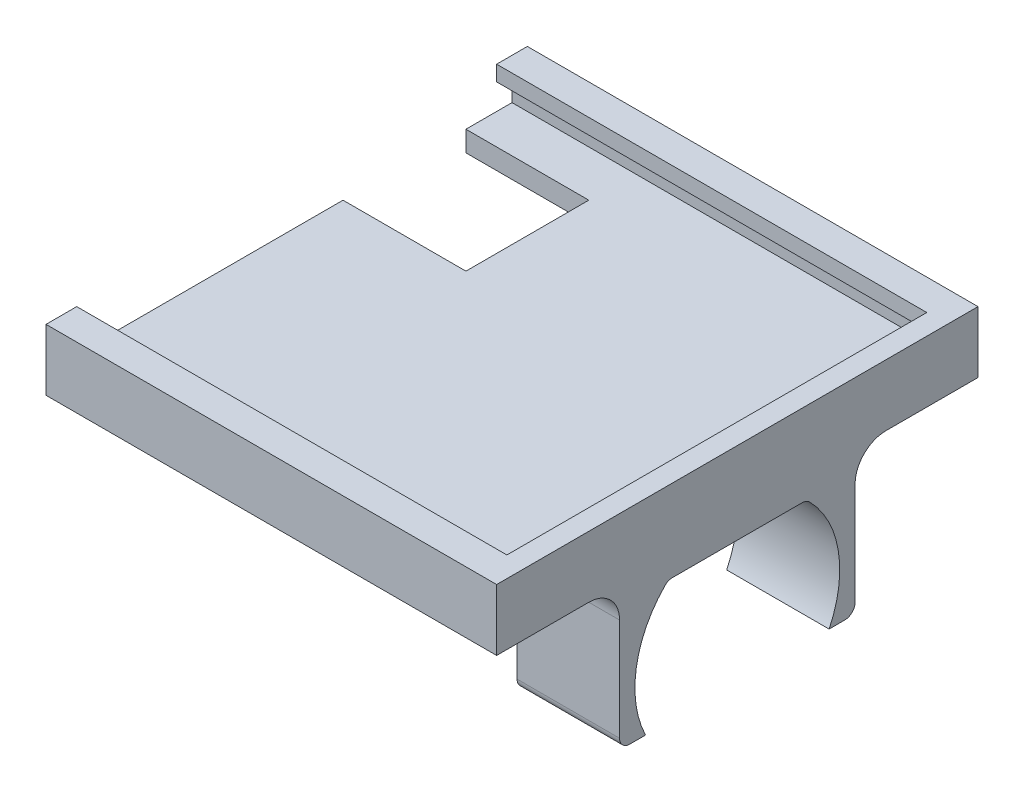
SolidWorks part; units mm, degrees
ref_plane "Front Plane" through (0, 0, 0) normal (0, 0, 1) x (1, 0, 0)
ref_plane "Top Plane" through (0, 0, 0) normal (0, 1, 0) x (1, 0, 0)
ref_plane "Right Plane" through (0, 0, 0) normal (1, 0, 0) x (0, 0, -1)
sketch "Sketch2" plane through (0, 0, 0) normal (0, 1, 0) x (1, 0, 0)
  line L1 (20, 21.5) -> (-20, 21.5)
  line L2 (20, 21.5) -> (20, -21.5)
  line L3 (20, -21.5) -> (-20, -21.5)
  line L4 (-20, 21.5) -> (-20, -21.5)
  line L5 (20, 21.5) -> (-20, -21.5) construction
  line L6 (20, -21.5) -> (-20, 21.5) construction
  point P0 (0, 0)
  dimension "D1" = 43
  dimension "D2" = 40
sketch "Sketch3" plane through (0, 0, 0) normal (0, 1, 0) x (1, 0, 0)
  line L0 (20, -21.5) -> (-20, 21.5) construction
  line L1 (-22, -23.5) -> (22, -23.5)
  line L2 (-22, -23.5) -> (-22, 23.5)
  line L3 (-22, 23.5) -> (22, 23.5)
  line L4 (22, -23.5) -> (22, 23.5)
  line L5 (-22, -23.5) -> (22, 23.5) construction
  line L6 (-22, 23.5) -> (22, -23.5) construction
  point P0 (0, 0)
  dimension "D1" = 47
  dimension "D2" = 44
extrude "Boss-Extrude1" add sketch "Sketch3" along normal blind 6
sketch "Sketch4" plane through (0, 6, 0) normal (0, 1, 0) x (1, 0, 0)
  line L1 (-22, -22) -> (20, -22)
  line L2 (-22, -22) -> (-22, 22)
  line L3 (-22, 22) -> (20, 22)
  line L4 (20, -22) -> (20, 22)
  line L5 (-22, 23.5) -> (-22, -23.5) construction
  line L7 (22, -23.5) -> (22, 23.5) construction
  line L8 (22, 23.5) -> (-22, 23.5) construction
  line L9 (-22, -23.5) -> (22, -23.5) construction
  dimension "D1" = 2
  dimension "D2" = 1.5
  dimension "D3" = 1.5
extrude "Cut-Extrude1" cut sketch "Sketch4" against normal blind 4 contours L3 L4 L1 L2
sketch "Sketch5" plane through (0, 6, 0) normal (0, 1, 0) x (1, 0, 0)
  line L0 (0, -3.3) -> (0, 3.3) construction
  line L1 (22, 20.5) -> (-22, 20.5)
  line L2 (22, 20.5) -> (22, 23.5)
  line L3 (22, 23.5) -> (-22, 23.5)
  line L4 (-22, 20.5) -> (-22, 23.5)
  line L5 (22, 20.5) -> (-22, 23.5) construction
  line L6 (22, 23.5) -> (-22, 20.5) construction
  line L7 (-22, 22) -> (20, 22) construction
  point P0 (0, 22)
extrude "Boss-Extrude2" add sketch "Sketch5" against normal blind 1.5
mirror "Mirror1" about plane through (0, 0, 0) normal (0, 0, 1) of "Boss-Extrude2"
sketch "Sketch6" plane through (0, 0, 0) normal (0, -1, 0) x (1, 0, 0)
  line L0 (-22, -23.5) -> (-22, 23.5) construction
  line L1 (-34, -17.5) -> (-10, -17.5)
  line L2 (-34, -17.5) -> (-34, -5.5)
  line L3 (-34, -5.5) -> (-10, -5.5)
  line L4 (-10, -17.5) -> (-10, -5.5)
  line L5 (-34, -17.5) -> (-10, -5.5) construction
  line L6 (-34, -5.5) -> (-10, -17.5) construction
  line L7 (22, -23.5) -> (-22, -23.5) construction
  point P0 (-22, -11.5)
  dimension "D1" = 6
  dimension "D2" = 12
  dimension "D3" = 12
extrude "Cut-Extrude2" cut sketch "Sketch6" against normal up to surface (2 mm away) up to face at (-1, 2, 0)
sketch "Sketch7" plane through (0, 0, 0) normal (1, 0, 0) x (0, 0, -1)
  line L0 (-6.75, -2) -> (6.75, -2)
  line L1 (0, 3.3) -> (0, -3.3) construction
  line L2 (24.2, 0) -> (-24.2, 0) construction
  line L3 (-10, -9.5) -> (10, -9.5) construction
  line L4 (-11.5, -14) -> (-8.9626, -14)
  line L5 (11.5, 0) -> (11.5, -14)
  line L6 (-21.5, 0) -> (21.5, 0) construction
  line L7 (-11.5, -14) -> (-11.5, 0)
  line L8 (21.5, 0) -> (-21.5, 0) construction
  line L9 (-11.5, 0) -> (11.5, 0)
  line L10 (8.9626, -14) -> (11.5, -14)
  arc A0 (-6.75, -2) -> (-8.9626, -14) centre (0.2788, -9.5) ccw
  arc A1 (8.9626, -14) -> (6.75, -2) centre (-0.2788, -9.5) ccw
  point P2 (0, -2)
  point P9 (0, -9.5)
  point P12 (11.2215, -14)
  point P13 (0, 0)
  dimension "D1" = 13.5
  dimension "D2" = 2
  dimension "D3" = 20
  dimension "D4" = 7.5
  dimension "D5" = 12
  dimension "D6" = 23
extrude "Boss-Extrude3" add sketch "Sketch7" against normal blind 10 from surface at 22 starting at face at (22, 3, 0)
fillet "Fillet1" radius 3 2 edges at (17, 0, 11.5) (17, 0, -11.5)
fillet "Fillet2" radius 1 4 edges at (17, -2, -6.75) (17, -2, 6.75) (17, -14, 11.5) (17, -14, -11.5)
